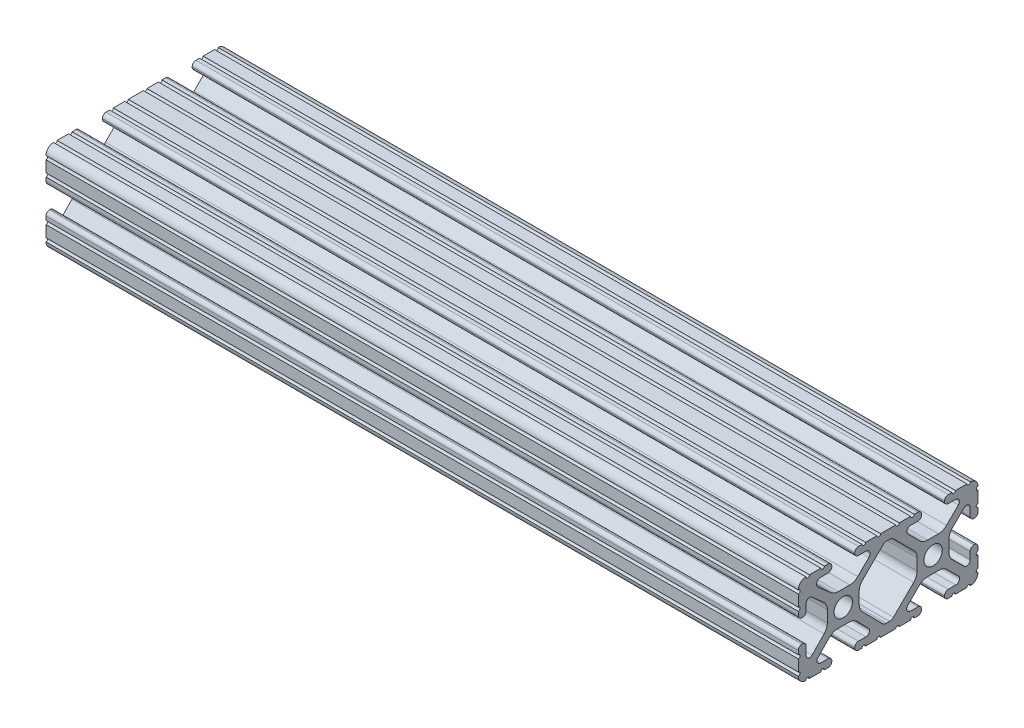
SolidWorks part; units mm, degrees
ref_plane "Front Plane" through (0, 0, 0) normal (0, 0, 1) x (1, 0, 0)
ref_plane "Top Plane" through (0, 0, 0) normal (0, 1, 0) x (1, 0, 0)
ref_plane "Right Plane" through (0, 0, 0) normal (1, 0, 0) x (0, 0, -1)
sketch "Sketch1" plane through (0, 0, 0) normal (0, 0, 1) x (1, 0, 0)
  line L0 (0, 0) -> (212.725, 0)
  dimension "D1" = 212.725
other "10 1020 PROFILE(1)"
ref_plane "Plane1" through (0, 0, 0) normal (1, 0, 0) x (0, 0, 1)
sketch "Sketch11" plane through (0, 0, 0) normal (1, 0, 0) x (0, 0, 1)
  line L1 (0, -12.7) -> (-25.4, -12.7) construction
  line L2 (0, -12.7) -> (0, 12.7) construction
  line L3 (0, 12.7) -> (-25.4, 12.7) construction
  line L4 (-25.4, -12.7) -> (-25.4, 12.7) construction
  line L5 (0, -12.7) -> (-25.4, 12.7) construction
  line L6 (0, 12.7) -> (-25.4, -12.7) construction
  line L7 (25.4, 12.7) -> (0, 12.7) construction
  line L8 (25.4, 12.7) -> (25.4, -12.7) construction
  line L9 (25.4, -12.7) -> (0, -12.7) construction
  line L10 (0, 12.7) -> (0, -12.7) construction
  line L11 (25.4, 12.7) -> (0, -12.7) construction
  line L12 (25.4, -12.7) -> (0, 12.7) construction
  line L17 (-8.1915, 1.6223) -> (-8.1915, -1.6223)
  line L18 (-1.504, 9.5765) -> (-7.252, 3.8768)
  line L19 (0.5515, 10.033) -> (-0.3952, 10.033)
  line L20 (7.2829, 3.8459) -> (1.6756, 9.5611)
  line L21 (8.1915, -1.6223) -> (8.1915, 1.6223)
  line L22 (1.5457, -9.5728) -> (7.2595, -3.8694)
  line L23 (-0.4332, -10.033) -> (0.4332, -10.033)
  line L24 (-7.2595, -3.8694) -> (-1.5457, -9.5728)
  line L136 (15.9385, 11.651) -> (15.9385, 11.5392)
  line L137 (16.9875, 10.4902) -> (19.1164, 10.4902)
  line L138 (19.8441, 8.7652) -> (16.619, 5.4551)
  line L139 (14.3449, 4.4958) -> (11.0833, 4.4958)
  line L140 (8.817, 5.4472) -> (5.5642, 8.7627)
  line L141 (6.2894, 10.4902) -> (8.4125, 10.4902)
  line L142 (9.4615, 11.5392) -> (9.4615, 11.651)
  line L143 (8.4125, 12.7) -> (7.3829, 12.7)
  line L144 (6.3669, 12.7) -> (3.1496, 12.7)
  line L145 (2.1336, 12.7) -> (-2.1336, 12.7)
  line L146 (-3.1496, 12.7) -> (-6.3669, 12.7)
  line L147 (-7.3829, 12.7) -> (-8.4125, 12.7)
  line L148 (-9.4615, 11.651) -> (-9.4615, 11.5392)
  line L149 (-8.4125, 10.4902) -> (-6.2836, 10.4902)
  line L150 (-5.5326, 8.6661) -> (-8.81, 5.4163)
  line L151 (-11.0455, 4.4958) -> (-14.3545, 4.4958)
  line L152 (-16.59, 5.4163) -> (-19.8674, 8.6661)
  line L153 (-19.1164, 10.4902) -> (-16.9875, 10.4902)
  line L154 (-15.9385, 11.5392) -> (-15.9385, 11.651)
  line L155 (-16.9875, 12.7) -> (-18.0171, 12.7)
  line L156 (-19.0331, 12.7) -> (-22.2504, 12.7)
  line L157 (-25.4, 9.5504) -> (-25.4, 6.3331)
  line L158 (-25.4, 5.3171) -> (-25.4, 4.2375)
  line L159 (-24.401, 3.2385) -> (-24.2392, 3.2385)
  line L160 (-23.1902, 4.2875) -> (-23.1902, 6.3347)
  line L161 (-21.434, 7.0665) -> (-18.148, 3.8082)
  line L162 (-17.2085, 1.5536) -> (-17.2085, -1.6952)
  line L163 (-18.1405, -3.9423) -> (-21.4316, -7.2274)
  line L164 (-23.1902, -6.498) -> (-23.1902, -4.2875)
  line L165 (-24.2392, -3.2385) -> (-24.351, -3.2385)
  line L166 (-25.4, -4.2875) -> (-25.4, -5.3171)
  line L167 (-25.4, -6.3331) -> (-25.4, -9.5504)
  line L168 (-22.2504, -12.7) -> (-19.0331, -12.7)
  line L169 (-18.0171, -12.7) -> (-16.9875, -12.7)
  line L170 (-15.9384, -11.651) -> (-15.9384, -11.5392)
  line L171 (-16.9875, -10.4902) -> (-19.1164, -10.4902)
  line L172 (-19.8341, -8.7551) -> (-16.4966, -5.4237)
  line L173 (-14.2536, -4.4958) -> (-11.1464, -4.4958)
  line L174 (-8.9034, -5.4237) -> (-5.5659, -8.7551)
  line L175 (-6.2836, -10.4902) -> (-8.4125, -10.4902)
  line L176 (-9.4616, -11.5392) -> (-9.4616, -11.651)
  line L177 (-8.4125, -12.7) -> (-7.3829, -12.7)
  line L178 (-6.3669, -12.7) -> (-3.1496, -12.7)
  line L179 (-2.1336, -12.7) -> (2.1336, -12.7)
  line L180 (3.1496, -12.7) -> (6.3669, -12.7)
  line L181 (7.3829, -12.7) -> (8.4125, -12.7)
  line L182 (9.4616, -11.651) -> (9.4616, -11.5392)
  line L183 (8.4125, -10.4902) -> (6.2894, -10.4902)
  line L184 (5.4807, -8.5353) -> (8.5979, -5.4237)
  line L185 (10.8409, -4.4958) -> (14.1026, -4.4958)
  line L186 (16.1879, -5.2766) -> (19.8682, -8.4822)
  line L187 (19.1164, -10.4902) -> (16.9875, -10.4902)
  line L188 (15.9384, -11.5392) -> (15.9384, -11.651)
  line L189 (16.9875, -12.7) -> (18.0171, -12.7)
  line L190 (19.0331, -12.7) -> (22.2504, -12.7)
  line L191 (25.4, -9.5504) -> (25.4, -6.3331)
  line L192 (25.4, -5.3171) -> (25.4, -4.2375)
  line L193 (24.401, -3.2385) -> (24.1892, -3.2385)
  line L194 (23.1902, -4.2375) -> (23.1902, -6.1559)
  line L195 (21.584, -6.8869) -> (18.2982, -4.025)
  line L196 (17.2085, -1.6308) -> (17.2085, 1.6308)
  line L197 (18.1094, 3.8465) -> (21.5263, 7.3534)
  line L198 (23.1902, 6.6769) -> (23.1902, 4.2375)
  line L199 (24.1892, 3.2385) -> (24.401, 3.2385)
  line L200 (25.4, 4.2375) -> (25.4, 5.3171)
  line L201 (25.4, 6.3332) -> (25.4, 9.5504)
  line L202 (22.2504, 12.7) -> (19.0331, 12.7)
  line L203 (18.0171, 12.7) -> (16.9875, 12.7)
  circle A1 centre (-12.7, 0) radius 2.6035
  circle A3 centre (12.7, 0) radius 2.6035
  arc A20 (-8.1915, -1.6223) -> (-7.2595, -3.8694) centre (-5.0165, -1.6223) ccw
  arc A21 (-7.252, 3.8768) -> (-8.1915, 1.6223) centre (-5.0165, 1.6223) ccw
  arc A22 (-0.3952, 10.033) -> (-1.504, 9.5765) centre (-0.3952, 8.4582) ccw
  arc A23 (1.6756, 9.5611) -> (0.5515, 10.033) centre (0.5515, 8.4582) ccw
  arc A24 (8.1915, 1.6223) -> (7.2829, 3.8459) centre (5.0165, 1.6223) ccw
  arc A25 (7.2595, -3.8694) -> (8.1915, -1.6223) centre (5.0165, -1.6223) ccw
  arc A26 (0.4332, -10.033) -> (1.5457, -9.5728) centre (0.4332, -8.4582) ccw
  arc A27 (-1.5457, -9.5728) -> (-0.4332, -10.033) centre (-0.4332, -8.4582) ccw
  arc A152 (16.9875, 12.7) -> (15.9385, 11.651) centre (16.9875, 11.651) ccw
  arc A153 (15.9385, 11.5392) -> (16.9875, 10.4902) centre (16.9875, 11.5392) ccw
  arc A154 (19.8441, 8.7652) -> (19.1164, 10.4902) centre (19.1164, 9.4742) ccw
  arc A155 (14.3449, 4.4958) -> (16.619, 5.4551) centre (14.3449, 7.6708) ccw
  arc A156 (8.817, 5.4472) -> (11.0833, 4.4958) centre (11.0833, 7.6708) ccw
  arc A157 (6.2894, 10.4902) -> (5.5642, 8.7627) centre (6.2894, 9.4742) ccw
  arc A158 (8.4125, 10.4902) -> (9.4615, 11.5392) centre (8.4125, 11.5392) ccw
  arc A159 (9.4615, 11.651) -> (8.4125, 12.7) centre (8.4125, 11.651) ccw
  arc A160 (6.3669, 12.7) -> (7.3829, 12.7) centre (6.8749, 12.7) ccw
  arc A161 (2.1336, 12.7) -> (3.1496, 12.7) centre (2.6416, 12.7) ccw
  arc A162 (-3.1496, 12.7) -> (-2.1336, 12.7) centre (-2.6416, 12.7) ccw
  arc A163 (-7.3829, 12.7) -> (-6.3669, 12.7) centre (-6.8749, 12.7) ccw
  arc A164 (-8.4125, 12.7) -> (-9.4615, 11.651) centre (-8.4125, 11.651) ccw
  arc A165 (-9.4615, 11.5392) -> (-8.4125, 10.4902) centre (-8.4125, 11.5392) ccw
  arc A166 (-5.5326, 8.6661) -> (-6.2836, 10.4902) centre (-6.2836, 9.4235) ccw
  arc A167 (-11.0455, 4.4958) -> (-8.81, 5.4163) centre (-11.0455, 7.6708) ccw
  arc A168 (-16.59, 5.4163) -> (-14.3545, 4.4958) centre (-14.3545, 7.6708) ccw
  arc A169 (-19.1164, 10.4902) -> (-19.8674, 8.6661) centre (-19.1164, 9.4235) ccw
  arc A170 (-16.9875, 10.4902) -> (-15.9385, 11.5392) centre (-16.9875, 11.5392) ccw
  arc A171 (-15.9385, 11.651) -> (-16.9875, 12.7) centre (-16.9875, 11.651) ccw
  arc A172 (-19.0331, 12.7) -> (-18.0171, 12.7) centre (-18.5251, 12.7) ccw
  arc A173 (-23.2664, 12.6998) -> (-22.2504, 12.7) centre (-22.7584, 12.7) ccw
  arc A174 (-23.2664, 12.6998) -> (-25.3998, 10.5664) centre (-23.2918, 10.5918) ccw
  arc A175 (-25.4, 9.5504) -> (-25.3998, 10.5664) centre (-25.4, 10.0584) ccw
  arc A176 (-25.4, 5.3171) -> (-25.4, 6.3331) centre (-25.4, 5.8251) ccw
  arc A177 (-25.4, 4.2375) -> (-24.401, 3.2385) centre (-24.401, 4.2375) ccw
  arc A178 (-24.2392, 3.2385) -> (-23.1902, 4.2875) centre (-24.2392, 4.2875) ccw
  arc A179 (-21.434, 7.0665) -> (-23.1902, 6.3347) centre (-22.1596, 6.3347) ccw
  arc A180 (-17.2085, 1.5536) -> (-18.148, 3.8082) centre (-20.3835, 1.5536) ccw
  arc A181 (-18.1405, -3.9423) -> (-17.2085, -1.6952) centre (-20.3835, -1.6952) ccw
  arc A182 (-23.1902, -6.498) -> (-21.4316, -7.2274) centre (-22.1596, -6.498) ccw
  arc A183 (-23.1902, -4.2875) -> (-24.2392, -3.2385) centre (-24.2392, -4.2875) ccw
  arc A184 (-24.351, -3.2385) -> (-25.4, -4.2875) centre (-24.351, -4.2875) ccw
  arc A185 (-25.4, -6.3331) -> (-25.4, -5.3171) centre (-25.4, -5.8251) ccw
  arc A186 (-25.3998, -10.5664) -> (-25.4, -9.5504) centre (-25.4, -10.0584) ccw
  arc A187 (-25.3998, -10.5664) -> (-23.2664, -12.6998) centre (-23.2918, -10.5918) ccw
  arc A188 (-22.2504, -12.7) -> (-23.2664, -12.6998) centre (-22.7584, -12.7) ccw
  arc A189 (-18.0171, -12.7) -> (-19.0331, -12.7) centre (-18.5251, -12.7) ccw
  arc A190 (-16.9875, -12.7) -> (-15.9384, -11.651) centre (-16.9875, -11.651) ccw
  arc A191 (-15.9384, -11.5392) -> (-16.9875, -10.4902) centre (-16.9875, -11.5392) ccw
  arc A192 (-19.8341, -8.7551) -> (-19.1164, -10.4902) centre (-19.1164, -9.4742) ccw
  arc A193 (-14.2536, -4.4958) -> (-16.4966, -5.4237) centre (-14.2536, -7.6708) ccw
  arc A194 (-8.9034, -5.4237) -> (-11.1464, -4.4958) centre (-11.1464, -7.6708) ccw
  arc A195 (-6.2836, -10.4902) -> (-5.5659, -8.7551) centre (-6.2836, -9.4742) ccw
  arc A196 (-8.4125, -10.4902) -> (-9.4616, -11.5392) centre (-8.4125, -11.5392) ccw
  arc A197 (-9.4616, -11.651) -> (-8.4125, -12.7) centre (-8.4125, -11.651) ccw
  arc A198 (-6.3669, -12.7) -> (-7.3829, -12.7) centre (-6.8749, -12.7) ccw
  arc A199 (-2.1336, -12.7) -> (-3.1496, -12.7) centre (-2.6416, -12.7) ccw
  arc A200 (3.1496, -12.7) -> (2.1336, -12.7) centre (2.6416, -12.7) ccw
  arc A201 (7.3829, -12.7) -> (6.3669, -12.7) centre (6.8749, -12.7) ccw
  arc A202 (8.4125, -12.7) -> (9.4616, -11.651) centre (8.4125, -11.651) ccw
  arc A203 (9.4616, -11.5392) -> (8.4125, -10.4902) centre (8.4125, -11.5392) ccw
  arc A204 (5.4807, -8.5353) -> (6.2894, -10.4902) centre (6.2894, -9.3455) ccw
  arc A205 (10.8409, -4.4958) -> (8.5979, -5.4237) centre (10.8409, -7.6708) ccw
  arc A206 (16.1879, -5.2766) -> (14.1026, -4.4958) centre (14.1026, -7.6708) ccw
  arc A207 (19.1164, -10.4902) -> (19.8682, -8.4822) centre (19.1164, -9.3455) ccw
  arc A208 (16.9875, -10.4902) -> (15.9384, -11.5392) centre (16.9875, -11.5392) ccw
  arc A209 (15.9384, -11.651) -> (16.9875, -12.7) centre (16.9875, -11.651) ccw
  arc A210 (19.0331, -12.7) -> (18.0171, -12.7) centre (18.5251, -12.7) ccw
  arc A211 (23.2664, -12.6998) -> (22.2504, -12.7) centre (22.7584, -12.7) ccw
  arc A212 (23.2664, -12.6998) -> (25.3998, -10.5664) centre (23.2918, -10.5918) ccw
  arc A213 (25.4, -9.5504) -> (25.3998, -10.5664) centre (25.4, -10.0584) ccw
  arc A214 (25.4, -5.3171) -> (25.4, -6.3331) centre (25.4, -5.8251) ccw
  arc A215 (25.4, -4.2375) -> (24.401, -3.2385) centre (24.401, -4.2375) ccw
  arc A216 (24.1892, -3.2385) -> (23.1902, -4.2375) centre (24.1892, -4.2375) ccw
  arc A217 (21.584, -6.8869) -> (23.1902, -6.1559) centre (22.2207, -6.1559) ccw
  arc A218 (17.2085, -1.6308) -> (18.2982, -4.025) centre (20.3835, -1.6308) ccw
  arc A219 (18.1094, 3.8465) -> (17.2085, 1.6308) centre (20.3835, 1.6308) ccw
  arc A220 (23.1902, 6.6769) -> (21.5263, 7.3534) centre (22.2207, 6.6769) ccw
  arc A221 (23.1902, 4.2375) -> (24.1892, 3.2385) centre (24.1892, 4.2375) ccw
  arc A222 (24.401, 3.2385) -> (25.4, 4.2375) centre (24.401, 4.2375) ccw
  arc A223 (25.4, 6.3332) -> (25.4, 5.3171) centre (25.4, 5.8251) ccw
  arc A224 (25.3998, 10.5664) -> (25.4, 9.5504) centre (25.4, 10.0584) ccw
  arc A225 (25.3998, 10.5664) -> (23.2664, 12.6998) centre (23.2918, 10.5918) ccw
  arc A226 (22.2504, 12.7) -> (23.2664, 12.6998) centre (22.7584, 12.7) ccw
  arc A227 (18.0171, 12.7) -> (19.0331, 12.7) centre (18.5251, 12.7) ccw
  point P3 (-12.7, 0)
  point P18 (0, 0)
  point P20 (0, 0)
  point P33 (12.7, 0)
  point P75 (12.7, -12.7)
  point P85 (25.4, 0)
  point P115 (12.7, 12.7)
  point P119 (-12.7, 12.7)
  point P122 (-25.4, 0)
  point P125 (-12.7, -12.7)
  point P128 (-25.4, -12.7)
  point P130 (-25.4, 12.7)
  point P133 (0, 12.7)
  point P137 (25.4, -12.7)
  point P140 (25.4, 12.7)
  point P143 (0, -12.7)
  dimension "D1" = 25.4
equation "\"D1@Sketch1\"=8in+(3/8)*1in"
